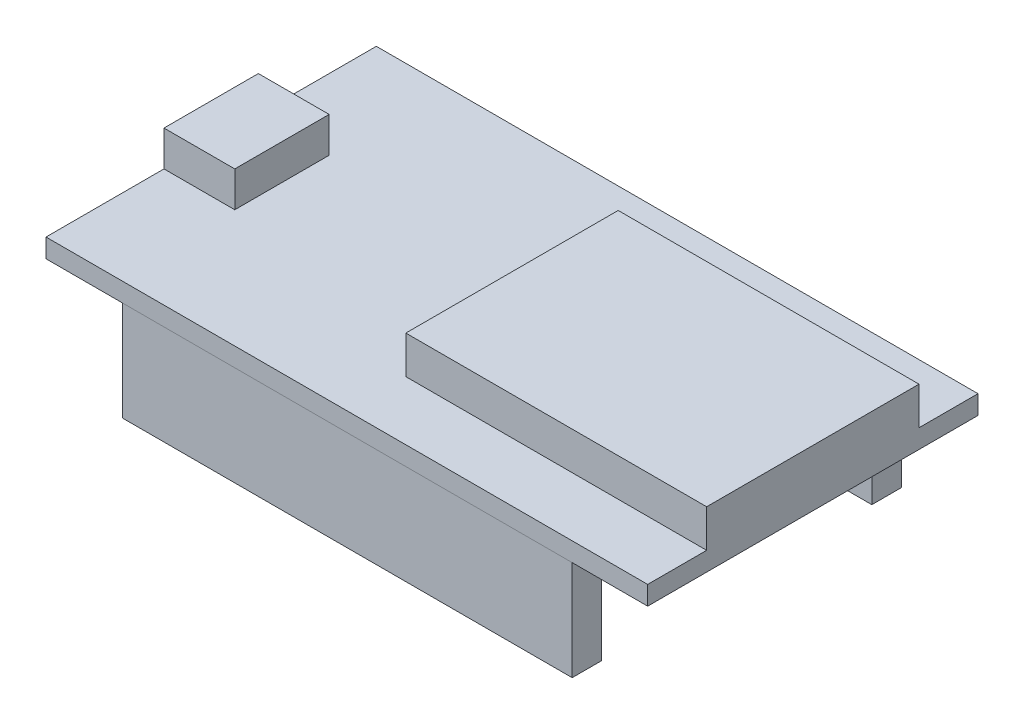
SolidWorks part; units mm, degrees
ref_plane "Front Plane" through (0, 0, 0) normal (0, 0, 1) x (1, 0, 0)
ref_plane "Top Plane" through (0, 0, 0) normal (0, 1, 0) x (1, 0, 0)
ref_plane "Right Plane" through (0, 0, 0) normal (1, 0, 0) x (0, 0, -1)
other "Configuration Table"
sketch "Sketch1" plane through (0, 0, 0) normal (0, 1, 0) x (1, 0, 0)
  line L1 (-25.5, -14) -> (25.5, -14)
  line L2 (-25.5, -14) -> (-25.5, 14)
  line L3 (-25.5, 14) -> (25.5, 14)
  line L4 (25.5, -14) -> (25.5, 14)
  line L5 (-25.5, -14) -> (25.5, 14) construction
  line L6 (-25.5, 14) -> (25.5, -14) construction
  point P6 (0, 0)
  dimension "D1" = 51
  dimension "D2" = 28
extrude "Board" add sketch "Sketch1" along normal blind 1.6
sketch "Sketch2" plane through (0, 0, 0) normal (0, 1, 0) x (1, 0, 0)
  line L0 (0, -9) -> (25.5, -9)
  line L1 (25.5, -9) -> (25.5, 9)
  line L2 (25.5, 9) -> (0, 9)
  line L3 (0, 9) -> (0, -9)
extrude "WROOM_Module" add sketch "Sketch2" along normal blind 3.2 from offset 1.6
sketch "Sketch3" plane through (0, 0, 0) normal (0, 1, 0) x (1, 0, 0)
  line L0 (-25.5, -4) -> (-19.5, -4)
  line L1 (-19.5, -4) -> (-19.5, 4)
  line L2 (-19.5, 4) -> (-25.5, 4)
  line L3 (-25.5, 4) -> (-25.5, -4)
extrude "Micro_USB" add sketch "Sketch3" along normal blind 3 from offset 1.6
sketch "Sketch4" plane through (0, 0, 0) normal (0, 1, 0) x (1, 0, 0)
  line L0 (-19.05, 11.45) -> (19.05, 11.45)
  line L1 (19.05, 11.45) -> (19.05, 13.95)
  line L2 (19.05, 13.95) -> (-19.05, 13.95)
  line L3 (-19.05, 13.95) -> (-19.05, 11.45)
extrude "Header_A" add sketch "Sketch4" along normal blind 8.5 from offset 8.5
sketch "Sketch5" plane through (0, 0, 0) normal (0, 1, 0) x (1, 0, 0)
  line L0 (-19.05, -13.95) -> (19.05, -13.95)
  line L1 (19.05, -13.95) -> (19.05, -11.45)
  line L2 (19.05, -11.45) -> (-19.05, -11.45)
  line L3 (-19.05, -11.45) -> (-19.05, -13.95)
extrude "Header_B" add sketch "Sketch5" along normal blind 8.5 from offset 8.5
equation "\"Jar_OD\"= 90  'ASSUMED - Part G fallback - jar outer diameter"
equation "\"Jar_H\"= 120  'ASSUMED - Part G fallback - jar height"
equation "\"Pump_L\"= 45  'ASSUMED - Part G fallback"
equation "\"Pump_W\"= 24  'ASSUMED - Part G fallback"
equation "\"Pump_H\"= 33  'ASSUMED - Part G fallback"
equation "\"Pump_Outlet_OD\"= 7.5  'ASSUMED - Part G fallback"
equation "\"Tube_OD\"= 8  'ASSUMED - Part G fallback"
equation "\"Tube_ID\"= 6  'ASSUMED - Part G fallback"
equation "\"TDS_Body_Dia\"= 12  'ASSUMED - Part G fallback"
equation "\"TDS_Wet_Len\"= 45  'ASSUMED - Part G fallback - length in water"
equation "\"DS_Tube_Dia\"= 6  'ASSUMED - Part G fallback"
equation "\"DS_Tube_Len\"= 50  'ASSUMED - Part G fallback"
equation "\"ORP_Body_Dia\"= 12  'ASSUMED - Part G fallback"
equation "\"ORP_Body_Len\"= 150  'ASSUMED - Part G fallback"
equation "\"ORP_Cap_Dia\"= 16  'ASSUMED - Part G fallback"
equation "\"Turb_W\"= 33  'ASSUMED - Part G fallback - head width"
equation "\"Turb_D\"= 28  'ASSUMED - Part G fallback - head depth"
equation "\"Turb_H\"= 30  'ASSUMED - Part G fallback - head height"
equation "\"Turb_Slot_W\"= 10  'ASSUMED - Part G fallback - slot width"
equation "\"Flow_L\"= 62  'ASSUMED - Part G fallback YF-S201"
equation "\"Flow_W\"= 36  'ASSUMED - Part G fallback"
equation "\"Flow_H\"= 35  'ASSUMED - Part G fallback"
equation "\"Thread_G12_OD\"= 20.955  'ASSUMED - Part G fallback thread G1/2 (major diameter)"
equation "\"Valve_L\"= 75  'ASSUMED - Part G fallback"
equation "\"Valve_W\"= 45  'ASSUMED - Part G fallback"
equation "\"Valve_H\"= 60  'ASSUMED - Part G fallback"
equation "\"Tee_L\"= 40  'ASSUMED - Part G fallback - overall length"
equation "\"Tee_Branch_L\"= 25  'ASSUMED - Part G fallback"
equation "\"Tee_OD\"= 12  'ASSUMED - Part G fallback"
equation "\"Cuv_W\"= 12.5  'ASSUMED - old R3 cuvette (station suppressed in SS4)"
equation "\"Cuv_D\"= 12.5  'ASSUMED - old R3 cuvette (station suppressed in SS4)"
equation "\"Cuv_H\"= 45  'ASSUMED - old R3 cuvette (station suppressed in SS4)"
equation "\"LED_Board_L\"= 20  'ASSUMED - Part G fallback"
equation "\"LED_Board_W\"= 20  'ASSUMED - Part G fallback - LED at centre"
equation "\"GUVA_L\"= 20  'ASSUMED - Part G fallback"
equation "\"GUVA_W\"= 12  'ASSUMED - Part G fallback - sensor at centre"
equation "\"Reed_L\"= 27  'ASSUMED - Part G fallback MC-38 half"
equation "\"Reed_W\"= 14  'ASSUMED - Part G fallback"
equation "\"Reed_H\"= 8  'ASSUMED - Part G fallback"
equation "\"ESP_L\"= 51  'ASSUMED - Part G fallback"
equation "\"ESP_W\"= 28  'ASSUMED - Part G fallback"
equation "\"TFT_L\"= 58  'ASSUMED - Part G fallback - board"
equation "\"TFT_W\"= 35  'ASSUMED - Part G fallback - board"
equation "\"TFT_Win_L\"= 35  'ASSUMED - Part G fallback - visible window"
equation "\"TFT_Win_W\"= 28  'ASSUMED - Part G fallback - visible window"
equation "\"Relay_L\"= 50  'ASSUMED - Part G fallback"
equation "\"Relay_W\"= 26  'ASSUMED - Part G fallback"
equation "\"Relay_H\"= 19  'ASSUMED - Part G fallback"
equation "\"Mosfet_L\"= 34  'ASSUMED - Part G fallback"
equation "\"Mosfet_W\"= 17  'ASSUMED - Part G fallback"
equation "\"Mosfet_H\"= 12  'ASSUMED - Part G fallback"
equation "\"TDS_Board_L\"= 42  'ASSUMED - Part G fallback"
equation "\"TDS_Board_W\"= 32  'ASSUMED - Part G fallback"
equation "\"Turb_Board_L\"= 38  'ASSUMED - Part G fallback"
equation "\"Turb_Board_W\"= 28  'ASSUMED - Part G fallback"
equation "\"BNC_Thread_Dia\"= 9.5  'ASSUMED - Part G fallback"
equation "\"Plate_L\"= 420  'ASSUMED - Part G fallback"
equation "\"Plate_W\"= 297  'ASSUMED - Part G fallback"
equation "\"Plate_T\"= 6  'ASSUMED - Part G fallback"
equation "\"Probe_Clr\"= 0.3  'DESIGN VALUE - Part C rule 3 - printed probe hole = diameter + 0.3"
equation "\"Cuv_Clr\"= 0.2  'DESIGN VALUE - Part C rule 3 - cuvette pocket = size + 0.2"
equation "\"Label_H\"= 0.6  'DESIGN VALUE - Part D - raised label height"
equation "\"D1@Sketch1\" = \"ESP_L\""
equation "\"D2@Sketch1\" = \"ESP_W\""
equation "\"Booster_L\"= 150  'ASSUMED - Part G fallback - booster pump"
equation "\"Booster_W\"= 95  'ASSUMED - Part G fallback"
equation "\"Booster_H\"= 100  'ASSUMED - Part G fallback"
equation "\"PTube_OD\"= 6.35  'ASSUMED - Part G fallback - product tube 1/4 inch"
equation "\"Qz_Out\"= 12  'ASSUMED - Part G fallback - quartz channel outside square"
equation "\"Qz_Path\"= 10  'ASSUMED - Part G fallback - quartz channel inside light path"
equation "\"Qz_L\"= 40  'ASSUMED - Part G fallback - quartz channel length"
equation "\"LED860_Dia\"= 5  'ASSUMED - Part G fallback - 860 nm LED"
equation "\"BPW_L\"= 5.4  'ASSUMED - Part G fallback - BPW34"
equation "\"BPW_W\"= 4.3  'ASSUMED - Part G fallback - BPW34"
equation "\"Cart_Dia\"= 50  'ASSUMED - Part G fallback - sediment and pre-carbon cartridges"
equation "\"Cart_L\"= 255  'ASSUMED - Part G fallback"
equation "\"UF_Dia\"= 50  'ASSUMED - Part G fallback - UF cartridge"
equation "\"UF_L\"= 260  'ASSUMED - Part G fallback"
equation "\"RO_Dia\"= 62  'ASSUMED - Part G fallback - RO membrane housing"
equation "\"RO_L\"= 300  'ASSUMED - Part G fallback"
equation "\"UVC_Dia\"= 40  'ASSUMED - Part G fallback - UV-C chamber"
equation "\"UVC_L\"= 300  'ASSUMED - Part G fallback"
equation "\"Tank_W\"= 260  'ASSUMED - Part G fallback - storage tank"
equation "\"Tank_D\"= 160  'ASSUMED - Part G fallback"
equation "\"Tank_H\"= 300  'ASSUMED - Part G fallback"
equation "\"Cab_W\"= 400  'ASSUMED - Part G fallback - purifier cabinet"
equation "\"Cab_D\"= 270  'ASSUMED - Part G fallback"
equation "\"Cab_H\"= 560  'ASSUMED - Part G fallback"
equation "\"ORP_Board_L\"= 40  'ASSUMED - Part G fallback - ORP buffer board"
equation "\"ORP_Board_W\"= 30  'ASSUMED - Part G fallback"
equation "\"Opt_Board_L\"= 50  'ASSUMED - Part G fallback - optical front-end board"
equation "\"Opt_Board_W\"= 40  'ASSUMED - Part G fallback"
equation "\"Buck_L\"= 43  'ASSUMED - Part G fallback - 12 V to 5 V buck module"
equation "\"Buck_W\"= 21  'ASSUMED - Part G fallback"
equation "\"Buck_H\"= 14  'ASSUMED - Part G fallback"
equation "\"BB_L\"= 165  'ASSUMED - Part G fallback - breadboard (As_Built_R3 only)"
equation "\"BB_W\"= 55  'ASSUMED - Part G fallback"
equation "\"BB_H\"= 10  'ASSUMED - Part G fallback"
